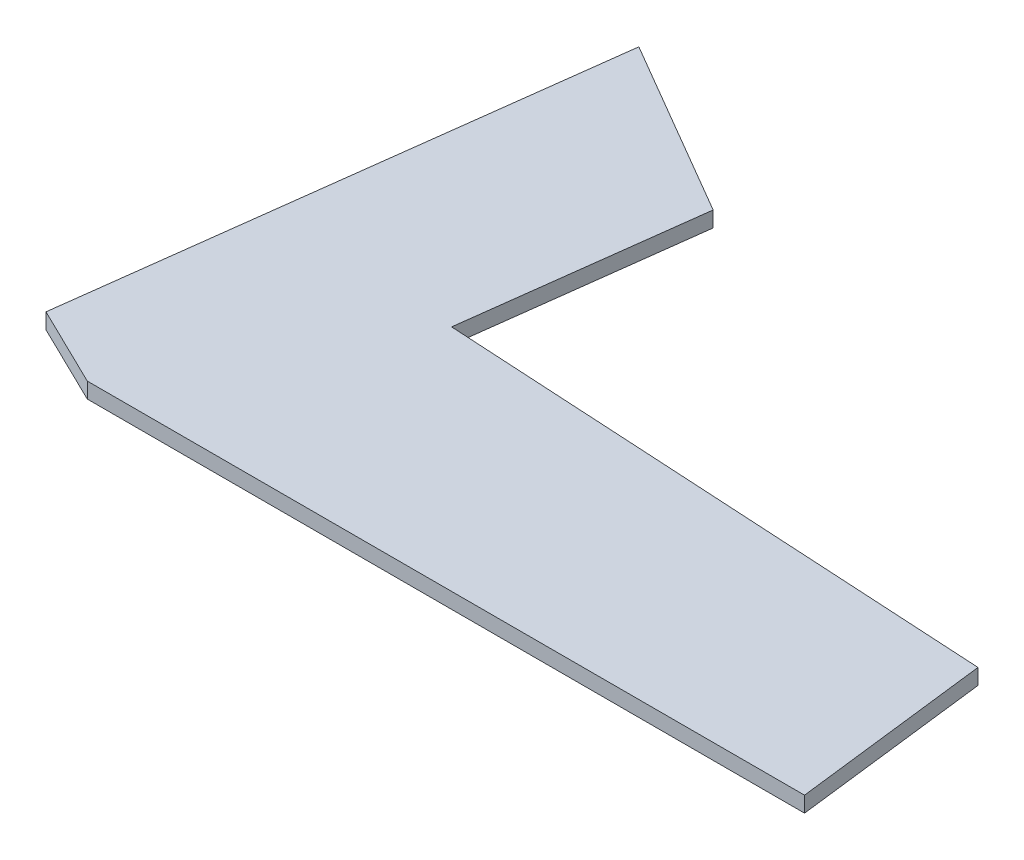
SolidWorks part; units mm, degrees
ref_plane "Front Plane" through (0, 0, 0) normal (0, 0, 1) x (1, 0, 0)
ref_plane "Top Plane" through (0, 0, 0) normal (0, 1, 0) x (1, 0, 0)
ref_plane "Right Plane" through (0, 0, 0) normal (1, 0, 0) x (0, 0, -1)
sketch "Sketch1" plane through (0, 0, 0) normal (0, 1, 0) x (1, 0, 0)
  line L0 (0, 0) -> (1.8935, 14.88)
  line L1 (1.8935, 14.88) -> (-9.5507, 21.5578)
  line L2 (-9.5507, 21.5578) -> (-13.8426, -12.1702)
  line L3 (-13.8426, -12.1702) -> (-8.6748, -14.6912)
  line L4 (-8.6748, -14.6912) -> (37.3252, -14.6912)
  line L5 (37.3252, -14.6912) -> (35.7923, -2.0337)
  line L6 (35.7923, -2.0337) -> (0, 0)
  point P7 (60.9033, -46.6814)
  point P9 (-5.6888, -30.9536)
  point P10 (-21.0819, -5.5215)
  point P11 (-5.0195, -21.5839)
  point P12 (67.596, -60.0667)
  point P13 (-16.6872, 11.0456)
  point P14 (-14.1792, 15.5738)
  point P15 (0, 0)
  point P16 (0, 0)
  point P17 (35.7923, -2.0337)
  dimension "D1" = 86
  dimension "D2" = 15
  dimension "D3" = 13.25
  dimension "D4" = 34
  dimension "D5" = 5.75
  dimension "D6" = 46
  dimension "D7" = 12.75
  dimension "D8" = 35.85
extrude "Boss-Extrude1" add sketch "Sketch1" along normal blind 1
